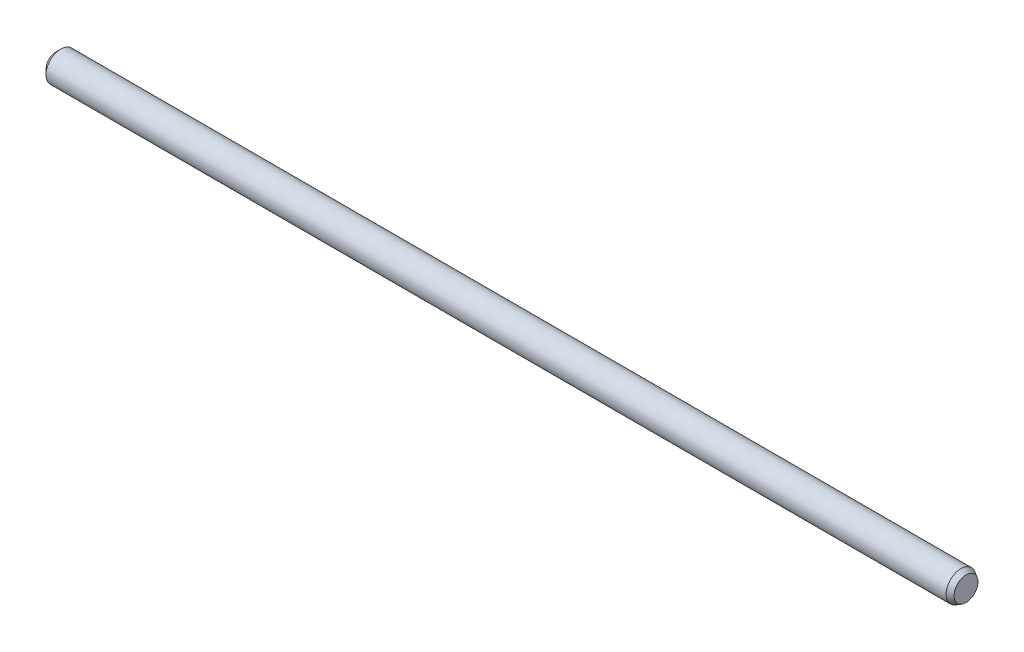
SolidWorks part; units mm, degrees
ref_plane "Alzado" through (0, 0, 0) normal (0, 0, 1) x (1, 0, 0)
ref_plane "Planta" through (0, 0, 0) normal (0, 1, 0) x (1, 0, 0)
ref_plane "Vista lateral" through (0, 0, 0) normal (1, 0, 0) x (0, 0, -1)
sketch "Croquis1" plane through (0, 0, 0) normal (1, 0, 0) x (0, 0, -1)
  circle A0 centre (0, 0) radius 1.475
  dimension "D1" = 2.95
extrude "Saliente-Extruir1" add sketch "Croquis1" along normal blind 90
chamfer "Chaflán1" distance 0.5 angle 30 1 edges at (90, 0, -1.475)
chamfer "Chaflán2" distance 0.5 angle 45 1 edges at (0, 0, -1.475)
